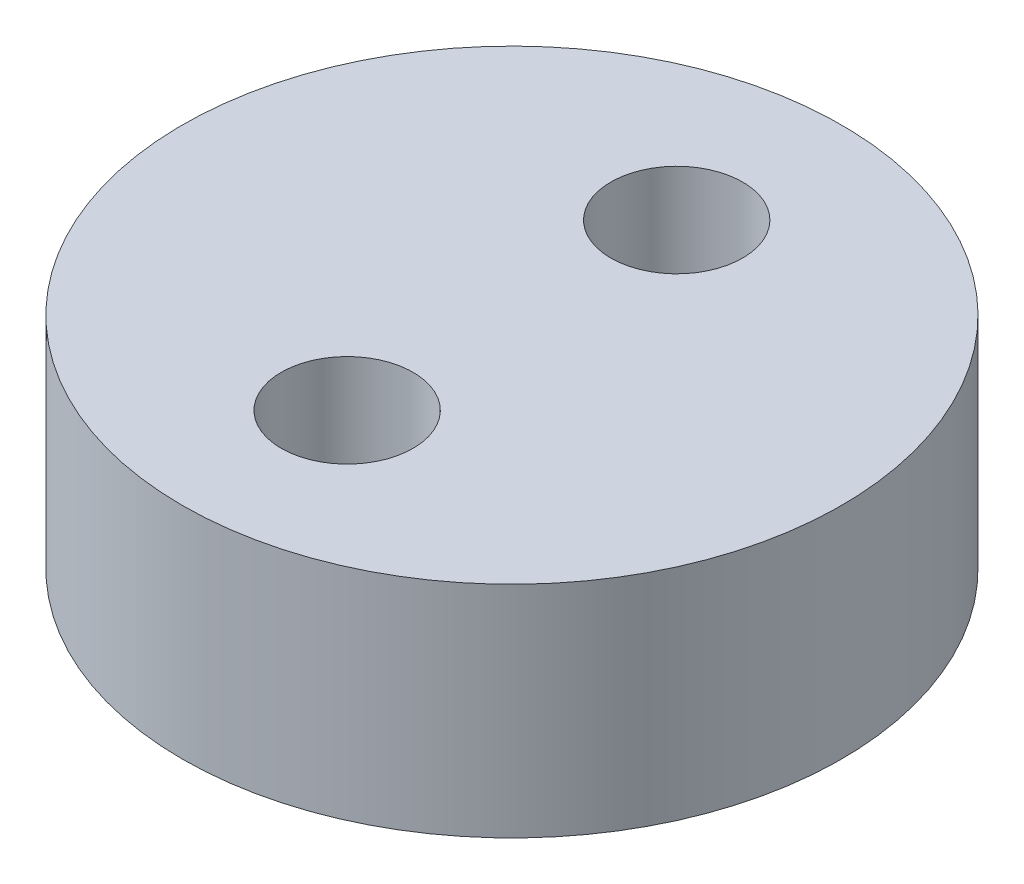
SolidWorks part; units mm, degrees
ref_plane "Front Plane" through (0, 0, 0) normal (0, 0, 1) x (1, 0, 0)
ref_plane "Top Plane" through (0, 0, 0) normal (0, 1, 0) x (1, 0, 0)
ref_plane "Right Plane" through (0, 0, 0) normal (1, 0, 0) x (0, 0, -1)
sketch "Sketch1" plane through (0, 0, 0) normal (0, 1, 0) x (1, 0, 0)
  circle A0 centre (0, 0) radius 15
  circle A1 centre (0, 7.5) radius 3
  circle A2 centre (0, -7.5) radius 3
  dimension "D1" = 30
  dimension "D2" = 7.5
  dimension "D3" = 7.5
extrude "Boss-Extrude1" add sketch "Sketch1" along normal blind 10
